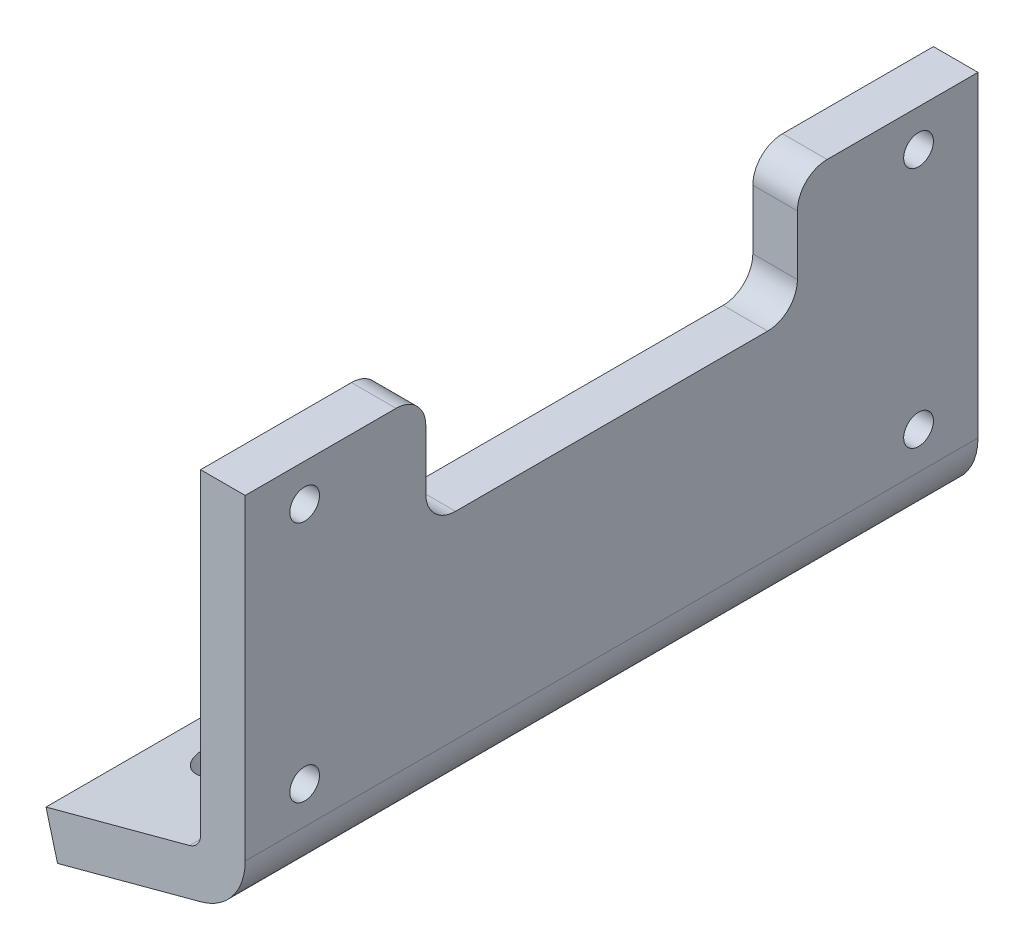
SolidWorks part; units mm, degrees
ref_plane "Front Plane" through (0, 0, 0) normal (0, 0, 1) x (1, 0, 0)
ref_plane "Top Plane" through (0, 0, 0) normal (0, 1, 0) x (1, 0, 0)
ref_plane "Right Plane" through (0, 0, 0) normal (1, 0, 0) x (0, 0, -1)
sketch "Sketch2" plane through (0, 0, 0) normal (0, 0, 1) x (1, 0, 0)
  line L0 (0, 0) -> (0, 16.3) construction
  line L1 (-2.2412, -1.9659) -> (-11.9004, -4.5541)
  line L2 (-1.5, 20.3) -> (1.5, 20.3)
  line L3 (-1.5, 20.3) -> (-1.5, -1)
  line L5 (1.5, 20.3) -> (1.5, -1)
  line L6 (-11.124, -7.4519) -> (-1.4647, -4.8637)
  line L7 (-11.9004, -4.5541) -> (-11.124, -7.4519)
  arc A0 (-1.5, -1) -> (-2.2412, -1.9659) centre (-2.5, -1) cw
  arc A1 (1.5, -1) -> (-1.4647, -4.8637) centre (-2.5, -1) cw
  point P7 (0, 20.3)
  dimension "D4" = 1
  dimension "D5" = 4
  dimension "D1" = 16.3
  dimension "D2" = 3
  dimension "D3" = 4
  dimension "D6" = 3
  dimension "D7" = 15
  dimension "D8" = 10
  dimension "D9" = 1
extrude "Boss-Extrude2" add sketch "Sketch2" along normal blind 49.3
sketch "Sketch3" plane through (1.5, 0, 0) normal (1, 0, 0) x (0, 0, -1)
  line L0 (-49.3, 20.3) -> (0, 20.3) construction
  line L1 (-45.3, 17.8) -> (-4, 17.8) construction
  line L2 (-45.3, 17.8) -> (-45.3, 1.5) construction
  line L3 (-45.3, 1.5) -> (-4, 1.5) construction
  line L4 (-4, 17.8) -> (-4, 1.5) construction
  line L5 (0, -1) -> (0, 20.3) construction
  circle A0 centre (-45.3, 17.8) radius 1
  circle A1 centre (-4, 17.8) radius 1
  circle A2 centre (-4, 1.5) radius 1
  circle A3 centre (-45.3, 1.5) radius 1
  point P4 (-24.65, 20.3)
  point P7 (-24.65, 17.8)
  point P10 (0, 9.65)
  point P11 (-4, 9.65)
  dimension "D3" = 2
  dimension "D1" = 41.3
  dimension "D2" = 16.3
extrude "Cut-Extrude1" cut sketch "Sketch3" against normal through all
sketch "Sketch4" plane through (0.3414, -1.2739, 0) normal (-0.2588, 0.9659, 0) x (0.9659, 0.2588, 0)
  line L0 (-2.6736, 0) -> (-12.6736, 0) construction
  line L1 (-2.6736, -49.3) -> (-12.6736, -49.3) construction
  line L2 (-12.6736, -49.3) -> (-12.6736, 0) construction
  circle A0 centre (-7.6736, -8) radius 2.25
  circle A1 centre (-7.6736, -41.3) radius 2.25
  dimension "D1" = 4.5
  dimension "D2" = 4.5
  dimension "D3" = 8
  dimension "D4" = 8
  dimension "D5" = 5
extrude "Cut-Extrude2" cut sketch "Sketch4" against normal through all
sketch "Sketch5" plane through (1.5, 0, 0) normal (1, 0, 0) x (0, 0, -1)
  line L0 (-49.3, 20.3) -> (0, 20.3) construction
  line L1 (-37.15, 20.3) -> (-12.15, 20.3)
  line L2 (-37.15, 20.3) -> (-37.15, 12.3)
  line L3 (-37.15, 12.3) -> (-12.15, 12.3)
  line L4 (-12.15, 20.3) -> (-12.15, 12.3)
  point P6 (-24.65, 20.3)
  point P7 (-24.65, 20.3)
  dimension "D1" = 25
  dimension "D2" = 8
extrude "Cut-Extrude3" cut sketch "Sketch5" against normal through all
fillet "Fillet1" radius 2 4 edges at (0, 20.3, 12.15) (0, 12.3, 12.15) (0, 12.3, 37.15) (0, 20.3, 37.15)
